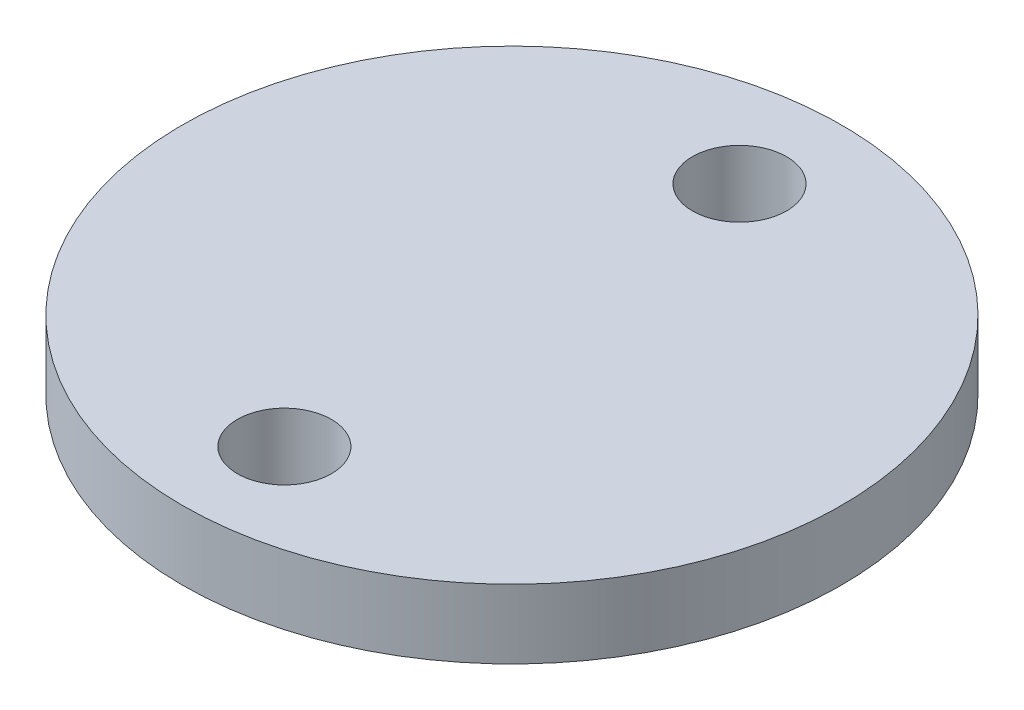
SolidWorks part; units mm, degrees
ref_plane "Front Plane" through (0, 0, 0) normal (0, 0, 1) x (1, 0, 0)
ref_plane "Top Plane" through (0, 0, 0) normal (0, 1, 0) x (1, 0, 0)
ref_plane "Right Plane" through (0, 0, 0) normal (1, 0, 0) x (0, 0, -1)
sketch "Sketch1" plane through (0, 0, 0) normal (0, 1, 0) x (1, 0, 0)
  circle A0 centre (0, 0) radius 10.5
  dimension "D1" = 21
extrude "Boss-Extrude1" add sketch "Sketch1" along normal blind 2.2
sketch "Sketch2" plane through (0, 2.2, 0) normal (0, 1, 0) x (1, 0, 0)
  line L0 (0, -16.0698) -> (0, 16.0698) construction
  line L1 (-27.9531, 0) -> (27.9531, 0) construction
  circle A2 centre (0, 7.25) radius 1.5
  circle A12 centre (0, -7.25) radius 1.5
  point P3 (0, 0)
  point P9 (0, 0)
  dimension "D1" = 3
  dimension "D2" = 7.25
extrude "Cut-Extrude1" cut sketch "Sketch2" against normal blind 2.2
sketch "Sketch3" plane through (0, 0, 0) normal (0, -1, 0) x (1, 0, 0)
  circle A0 centre (0, 0) radius 4.5
  dimension "D1" = 9
extrude "Boss-Extrude2" add sketch "Sketch3" along normal blind 4
sketch "Sketch4" plane through (0, -4, 0) normal (0, -1, 0) x (1, 0, 0)
  line L0 (0.5464, 2.9498) -> (0.4005, 1.962)
  line L1 (-0.2044, 2.993) -> (-0.1, 2)
  line L2 (0.2044, 2.993) -> (0.1, 2)
  line L3 (0.9423, 2.8482) -> (0.5942, 1.9123)
  line L4 (1.2628, 2.7213) -> (0.8759, 1.8008)
  line L5 (1.621, 2.5244) -> (1.0511, 1.7044)
  line L6 (1.8999, 2.3217) -> (1.2962, 1.5264)
  line L7 (2.1979, 2.0419) -> (1.442, 1.3895)
  line L8 (2.4176, 1.7763) -> (1.6351, 1.1561)
  line L9 (2.6366, 1.4312) -> (1.7422, 0.9872)
  line L10 (2.7834, 1.1193) -> (1.8712, 0.7131)
  line L11 (2.9097, 0.7305) -> (1.933, 0.5229)
  line L12 (2.9743, 0.3919) -> (1.9898, 0.2254)
  line L13 (3, -0.016) -> (2.0023, 0.0258)
  line L14 (2.9783, -0.3601) -> (1.9833, -0.2765)
  line L15 (2.9017, -0.7616) -> (1.9458, -0.473)
  line L16 (2.7952, -1.0894) -> (1.8522, -0.7611)
  line L17 (2.6212, -1.4593) -> (1.7671, -0.942)
  line L18 (2.4364, -1.7504) -> (1.6048, -1.1978)
  line L19 (2.1759, -2.0653) -> (1.4773, -1.3519)
  line L20 (1.9246, -2.3013) -> (1.2565, -1.5593)
  line L21 (1.5939, -2.5415) -> (1.0947, -1.6768)
  line L22 (1.2918, -2.7076) -> (0.8292, -1.8227)
  line L23 (0.9118, -2.8581) -> (0.6433, -1.8964)
  line L24 (0.5779, -2.9438) -> (0.3499, -1.9717)
  line L25 (0.1724, -2.995) -> (0.1515, -1.9968)
  line L26 (-0.1724, -2.995) -> (-0.1515, -1.9968)
  line L27 (-0.5779, -2.9438) -> (-0.3499, -1.9717)
  line L28 (-0.9118, -2.8581) -> (-0.6433, -1.8964)
  line L29 (-1.2918, -2.7076) -> (-0.8292, -1.8227)
  line L30 (-1.5939, -2.5415) -> (-1.0947, -1.6768)
  line L31 (-1.9246, -2.3013) -> (-1.2565, -1.5593)
  line L32 (-2.1759, -2.0653) -> (-1.4773, -1.3519)
  line L33 (-2.4364, -1.7504) -> (-1.6048, -1.1978)
  line L34 (-2.6212, -1.4593) -> (-1.7671, -0.942)
  line L35 (-2.7952, -1.0894) -> (-1.8522, -0.7611)
  line L36 (-2.9017, -0.7616) -> (-1.9458, -0.473)
  line L37 (-2.9783, -0.3601) -> (-1.9833, -0.2765)
  line L38 (-3, -0.016) -> (-2.0023, 0.0258)
  line L39 (-2.9743, 0.3919) -> (-1.9898, 0.2254)
  line L40 (-2.9097, 0.7305) -> (-1.933, 0.5229)
  line L41 (-2.7834, 1.1193) -> (-1.8712, 0.7131)
  line L42 (-2.6366, 1.4312) -> (-1.7422, 0.9872)
  line L43 (-2.4176, 1.7763) -> (-1.6351, 1.1561)
  line L44 (-2.1979, 2.0419) -> (-1.442, 1.3895)
  line L45 (-1.8999, 2.3217) -> (-1.2962, 1.5264)
  line L46 (-1.621, 2.5244) -> (-1.0511, 1.7044)
  line L47 (-1.2628, 2.7213) -> (-0.8759, 1.8008)
  line L48 (-0.9423, 2.8482) -> (-0.5942, 1.9123)
  line L49 (-0.5464, 2.9498) -> (-0.4005, 1.962)
  circle A0 centre (0, 0) radius 3
  circle A1 centre (0, 0) radius 2 construction
  arc A2 (-0.1, 2) -> (0.1, 2) centre (0, 2) ccw
  arc A3 (0.4005, 1.962) -> (0.5942, 1.9123) centre (0.4974, 1.9372) ccw
  arc A4 (0.8759, 1.8008) -> (1.0511, 1.7044) centre (0.9635, 1.7526) ccw
  arc A5 (1.2962, 1.5264) -> (1.442, 1.3895) centre (1.3691, 1.4579) ccw
  arc A6 (1.6351, 1.1561) -> (1.7422, 0.9872) centre (1.6887, 1.0717) ccw
  arc A7 (1.8712, 0.7131) -> (1.933, 0.5229) centre (1.9021, 0.618) ccw
  arc A8 (1.9898, 0.2254) -> (2.0023, 0.0258) centre (1.9961, 0.1256) ccw
  arc A9 (1.9833, -0.2765) -> (1.9458, -0.473) centre (1.9646, -0.3748) ccw
  arc A10 (1.8522, -0.7611) -> (1.7671, -0.942) centre (1.8097, -0.8516) ccw
  arc A11 (1.6048, -1.1978) -> (1.4773, -1.3519) centre (1.541, -1.2748) ccw
  arc A12 (1.2565, -1.5593) -> (1.0947, -1.6768) centre (1.1756, -1.618) ccw
  arc A13 (0.8292, -1.8227) -> (0.6433, -1.8964) centre (0.7362, -1.8596) ccw
  arc A14 (0.3499, -1.9717) -> (0.1515, -1.9968) centre (0.2507, -1.9842) ccw
  arc A15 (-0.1515, -1.9968) -> (-0.3499, -1.9717) centre (-0.2507, -1.9842) ccw
  arc A16 (-0.6433, -1.8964) -> (-0.8292, -1.8227) centre (-0.7362, -1.8596) ccw
  arc A17 (-1.0947, -1.6768) -> (-1.2565, -1.5593) centre (-1.1756, -1.618) ccw
  arc A18 (-1.4773, -1.3519) -> (-1.6048, -1.1978) centre (-1.541, -1.2748) ccw
  arc A19 (-1.7671, -0.942) -> (-1.8522, -0.7611) centre (-1.8097, -0.8516) ccw
  arc A20 (-1.9458, -0.473) -> (-1.9833, -0.2765) centre (-1.9646, -0.3748) ccw
  arc A21 (-2.0023, 0.0258) -> (-1.9898, 0.2254) centre (-1.9961, 0.1256) ccw
  arc A22 (-1.933, 0.5229) -> (-1.8712, 0.7131) centre (-1.9021, 0.618) ccw
  arc A23 (-1.7422, 0.9872) -> (-1.6351, 1.1561) centre (-1.6887, 1.0717) ccw
  arc A24 (-1.442, 1.3895) -> (-1.2962, 1.5264) centre (-1.3691, 1.4579) ccw
  arc A25 (-1.0511, 1.7044) -> (-0.8759, 1.8008) centre (-0.9635, 1.7526) ccw
  arc A26 (-0.5942, 1.9123) -> (-0.4005, 1.962) centre (-0.4974, 1.9372) ccw
  dimension "D1" = 6
  dimension "D2" = 4
  dimension "D3" = 0.2
  dimension "D4" = 25
extrude "Cut-Extrude5" cut sketch "Sketch4" against normal blind 4 contours A26 L48 A0 L47 A25 L46 L45 A24 L44 L43 A23 L42 L41 A22 L40 L39 A21 L38 L37 A20 L36 L35 A19 L34 L33 A18 L32 L31 A17 L30 L29 A16 L28 L27 A15 L26 L25 A14 L24
sketch "Sketch5" plane through (0, -4, 0) normal (0, -1, 0) x (1, 0, 0)
  circle A0 centre (0, 0) radius 2.5
  dimension "D1" = 5
extrude "Cut-Extrude6" cut sketch "Sketch5" against normal blind 4
fillet "Fillet1" radius 0.1 50 edges at (2.0254, -2, 1.4655) (2.1884, -2, 1.2087) (1.5973, -2, 1.9231) (1.819, -2, 1.715) (2.3262, -2, 0.9157) (2.4202, -2, 0.6265) (2.4809, -2, 0.3085) (2.5, -2, 0.0049) (2.4797, -2, -0.3182) (2.4227, -2, -0.617) (2.3226, -2, -0.9249) (2.1931, -2, -1.2001) (1.8258, -2, -1.7078) (2.0196, -2, -1.4734) (1.3437, -2, -2.1082) (1.5898, -2, -1.9294) (0.7772, -2, -2.3761) (1.06, -2, -2.2642) (0.1619, -2, -2.4948) (0.4636, -2, -2.4566) (-0.4636, -2, -2.4566) (-0.1619, -2, -2.4948) (-1.06, -2, -2.2642) (-0.7772, -2, -2.3761) (-1.5898, -2, -1.9294) (-1.3437, -2, -2.1082) (-2.0196, -2, -1.4734) (-1.8258, -2, -1.7078) (-2.3226, -2, -0.9249) (-2.1931, -2, -1.2001) (-2.4797, -2, -0.3182) (-2.4227, -2, -0.617) (-2.4809, -2, 0.3085) (-2.5, -2, 0.0049) (1.3354, -2, 2.1135) (1.0689, -2, 2.26) (0.7679, -2, 2.3792) (0.4733, -2, 2.4548) (0.1521, -2, 2.4954) (-0.1521, -2, 2.4954) (-2.3262, -2, 0.9157) (-2.4202, -2, 0.6265) (-2.0254, -2, 1.4655) (-2.1884, -2, 1.2087) (-0.4733, -2, 2.4548) (-0.7679, -2, 2.3792) (-1.0689, -2, 2.26) (-1.3354, -2, 2.1135) (-1.5973, -2, 1.9231) (-1.819, -2, 1.715)
